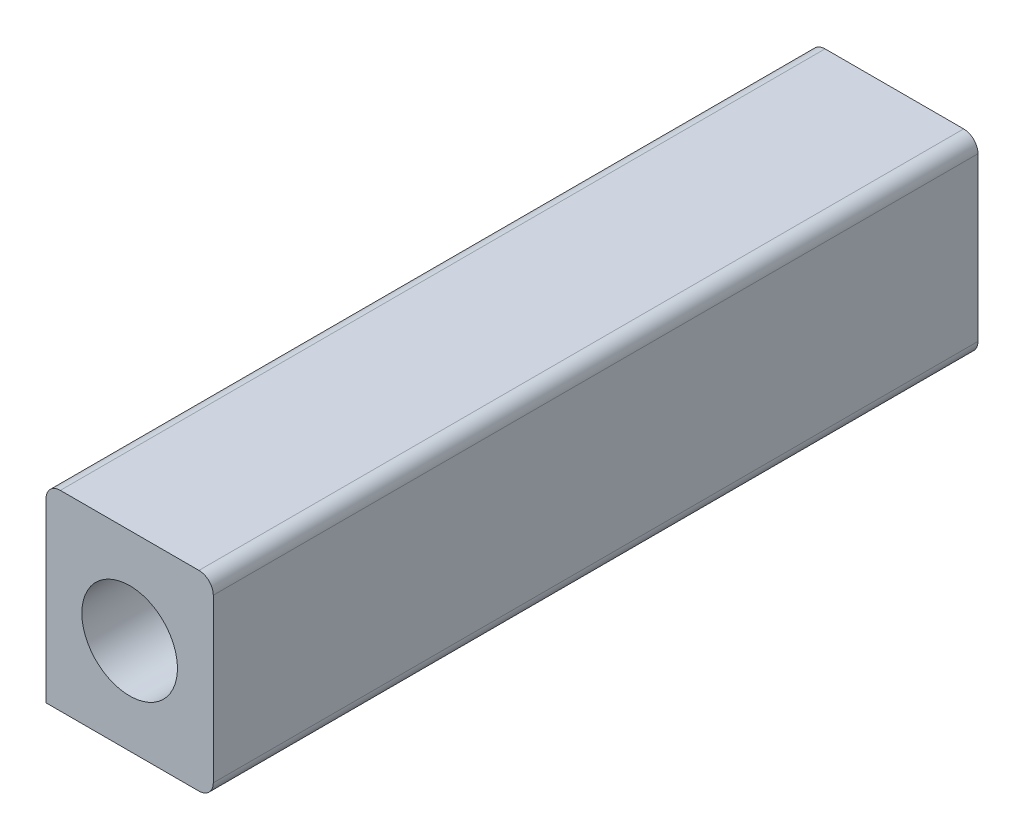
SolidWorks part; units mm, degrees
ref_plane "前视基准面" through (0, 0, 0) normal (0, 0, 1) x (1, 0, 0)
ref_plane "上视基准面" through (0, 0, 0) normal (0, 1, 0) x (1, 0, 0)
ref_plane "右视基准面" through (0, 0, 0) normal (1, 0, 0) x (0, 0, -1)
other "Configuration Table"
sketch "草图8" plane through (0, 0, 0) normal (0, 0, 1) x (1, 0, 0)
  line L0 (-35, -40) -> (35, -40)
  line L1 (35, -40) -> (35, 40)
  line L2 (35, 40) -> (-35, 40)
  line L3 (-35, 40) -> (-35, -40)
extrude "凸台-拉伸1" add sketch "草图8" along normal blind 320
sketch "草图9" plane through (0, 0, 0) normal (0, 0, -1) x (-1, 0, 0)
  circle A0 centre (0, 0) radius 20
extrude "切除-拉伸1" cut sketch "草图9" against normal through all
fillet "圆角1" radius 6 3 edges at (35, -40, 160) (-35, 40, 160) (35, 40, 160)
